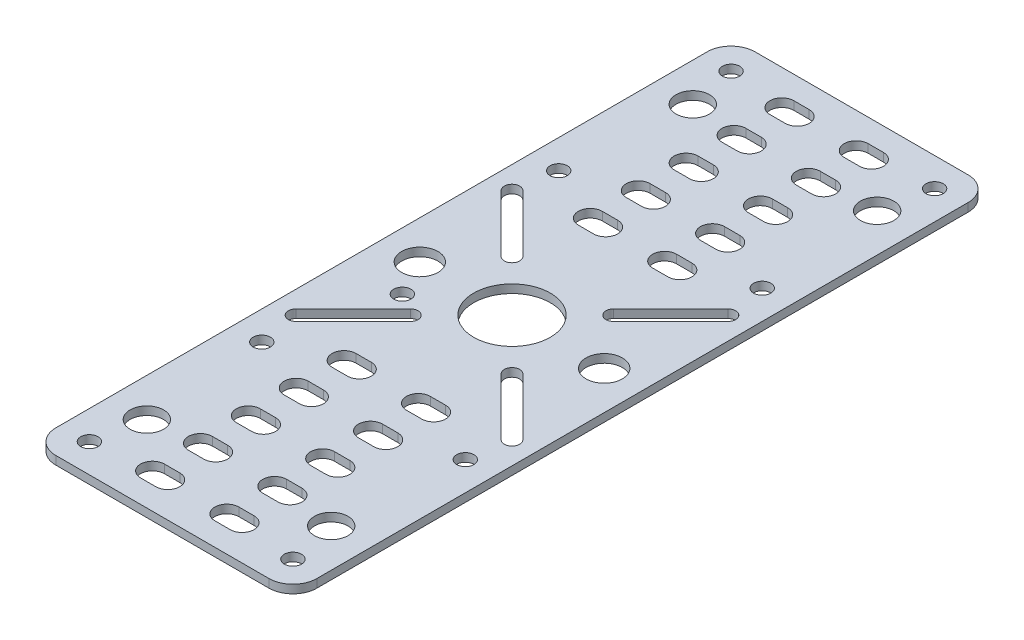
SolidWorks part; units mm, degrees
ref_plane "Front Plane" through (0, 0, 0) normal (0, 0, 1) x (1, 0, 0)
ref_plane "Top Plane" through (0, 0, 0) normal (0, 1, 0) x (1, 0, 0)
ref_plane "Right Plane" through (0, 0, 0) normal (1, 0, 0) x (0, 0, -1)
sketch "Sketch1" plane through (0, 0, 0) normal (0, 1, 0) x (1, 0, 0)
  line L1 (-27.25, 73) -> (27.25, 73)
  line L3 (-27.25, -73) -> (27.25, -73)
  line L5 (-27.25, 73) -> (27.25, -73) construction
  line L6 (-27.25, -73) -> (27.25, 73) construction
  line L9 (-27.25, 73) -> (-27.25, -73)
  line L13 (27.25, 73) -> (27.25, -73)
  point P0 (0, 0)
  dimension "D1" = 54.5
  dimension "D2" = 146
extrude "Boss-Extrude1" add sketch "Sketch1" along normal blind 1.75
sketch "Sketch2" plane through (0, 1.75, 0) normal (0, 1, 0) x (1, 0, 0)
  line L0 (0, 0) -> (-64.534, 64.534) construction
  line L1 (0, 0) -> (0, 55.3558) construction
  line L2 (0, 0) -> (-65.3333, 0) construction
  line L3 (-10.6066, 10.6066) -> (-22.55, 22.55) construction
  line L4 (-11.738, 9.4752) -> (-23.6814, 21.4186)
  line L5 (-9.4752, 11.738) -> (-21.4186, 23.6814)
  line L6 (10.6066, 10.6066) -> (22.55, 22.55) construction
  line L7 (11.738, 9.4752) -> (23.6814, 21.4186)
  line L8 (9.4752, 11.738) -> (21.4186, 23.6814)
  line L9 (-10.6066, -10.6066) -> (-22.55, -22.55) construction
  line L10 (-11.738, -9.4752) -> (-23.6814, -21.4186)
  line L11 (-9.4752, -11.738) -> (-21.4186, -23.6814)
  line L12 (10.6066, -10.6066) -> (22.55, -22.55) construction
  line L13 (11.738, -9.4752) -> (23.6814, -21.4186)
  line L14 (9.4752, -11.738) -> (21.4186, -23.6814)
  line L15 (-9.3578, 65.7099) -> (-6.1612, 65.7099) construction
  line L16 (-9.3578, 68.2099) -> (-6.1612, 68.2099)
  line L17 (-9.3578, 63.2099) -> (-6.1612, 63.2099)
  line L18 (-9.3578, 55.7099) -> (-6.1612, 55.7099) construction
  line L19 (-9.3578, 58.2099) -> (-6.1612, 58.2099)
  line L20 (-9.3578, 53.2099) -> (-6.1612, 53.2099)
  line L21 (9.3578, 55.7099) -> (6.1612, 55.7099) construction
  line L22 (9.3578, 58.2099) -> (6.1612, 58.2099)
  line L23 (9.3578, 53.2099) -> (6.1612, 53.2099)
  line L24 (-9.3578, 45.7099) -> (-6.1612, 45.7099) construction
  line L25 (-9.3578, 48.2099) -> (-6.1612, 48.2099)
  line L26 (-9.3578, 43.2099) -> (-6.1612, 43.2099)
  line L27 (9.3578, 45.7099) -> (6.1612, 45.7099) construction
  line L28 (9.3578, 48.2099) -> (6.1612, 48.2099)
  line L29 (9.3578, 43.2099) -> (6.1612, 43.2099)
  line L30 (-9.3578, 35.7099) -> (-6.1612, 35.7099) construction
  line L31 (-9.3578, 38.2099) -> (-6.1612, 38.2099)
  line L32 (-9.3578, 33.2099) -> (-6.1612, 33.2099)
  line L33 (9.3578, 65.7099) -> (6.1612, 65.7099) construction
  line L34 (9.3578, 68.2099) -> (6.1612, 68.2099)
  line L35 (9.3578, 63.2099) -> (6.1612, 63.2099)
  line L36 (9.3578, 35.7099) -> (6.1612, 35.7099) construction
  line L37 (9.3578, 38.2099) -> (6.1612, 38.2099)
  line L38 (9.3578, 33.2099) -> (6.1612, 33.2099)
  line L39 (-9.3578, 25.7099) -> (-6.1612, 25.7099) construction
  line L40 (-9.3578, 28.2099) -> (-6.1612, 28.2099)
  line L41 (-9.3578, 23.2099) -> (-6.1612, 23.2099)
  line L42 (9.3578, 25.7099) -> (6.1612, 25.7099) construction
  line L43 (9.3578, 28.2099) -> (6.1612, 28.2099)
  line L44 (9.3578, 23.2099) -> (6.1612, 23.2099)
  line L45 (-9.3578, -65.7099) -> (-6.1612, -65.7099) construction
  line L46 (-9.3578, -68.2099) -> (-6.1612, -68.2099)
  line L47 (-9.3578, -63.2099) -> (-6.1612, -63.2099)
  line L48 (-9.3578, -55.7099) -> (-6.1612, -55.7099) construction
  line L49 (-9.3578, -58.2099) -> (-6.1612, -58.2099)
  line L50 (-9.3578, -53.2099) -> (-6.1612, -53.2099)
  line L51 (9.3578, -55.7099) -> (6.1612, -55.7099) construction
  line L52 (9.3578, -58.2099) -> (6.1612, -58.2099)
  line L53 (9.3578, -53.2099) -> (6.1612, -53.2099)
  line L54 (-9.3578, -45.7099) -> (-6.1612, -45.7099) construction
  line L55 (-9.3578, -48.2099) -> (-6.1612, -48.2099)
  line L56 (-9.3578, -43.2099) -> (-6.1612, -43.2099)
  line L57 (9.3578, -45.7099) -> (6.1612, -45.7099) construction
  line L58 (9.3578, -48.2099) -> (6.1612, -48.2099)
  line L59 (9.3578, -43.2099) -> (6.1612, -43.2099)
  line L60 (-9.3578, -35.7099) -> (-6.1612, -35.7099) construction
  line L61 (-9.3578, -38.2099) -> (-6.1612, -38.2099)
  line L62 (-9.3578, -33.2099) -> (-6.1612, -33.2099)
  line L63 (9.3578, -65.7099) -> (6.1612, -65.7099) construction
  line L64 (9.3578, -68.2099) -> (6.1612, -68.2099)
  line L65 (9.3578, -63.2099) -> (6.1612, -63.2099)
  line L66 (9.3578, -35.7099) -> (6.1612, -35.7099) construction
  line L67 (9.3578, -38.2099) -> (6.1612, -38.2099)
  line L68 (9.3578, -33.2099) -> (6.1612, -33.2099)
  line L69 (-9.3578, -25.7099) -> (-6.1612, -25.7099) construction
  line L70 (-9.3578, -28.2099) -> (-6.1612, -28.2099)
  line L71 (-9.3578, -23.2099) -> (-6.1612, -23.2099)
  line L72 (9.3578, -25.7099) -> (6.1612, -25.7099) construction
  line L73 (9.3578, -28.2099) -> (6.1612, -28.2099)
  line L74 (9.3578, -23.2099) -> (6.1612, -23.2099)
  arc A0 (-11.738, 9.4752) -> (-9.4752, 11.738) centre (-10.6066, 10.6066) ccw
  arc A1 (-21.4186, 23.6814) -> (-23.6814, 21.4186) centre (-22.55, 22.55) ccw
  arc A2 (11.738, 9.4752) -> (9.4752, 11.738) centre (10.6066, 10.6066) cw
  arc A3 (21.4186, 23.6814) -> (23.6814, 21.4186) centre (22.55, 22.55) cw
  arc A4 (-11.738, -9.4752) -> (-9.4752, -11.738) centre (-10.6066, -10.6066) cw
  arc A5 (-21.4186, -23.6814) -> (-23.6814, -21.4186) centre (-22.55, -22.55) cw
  arc A6 (11.738, -9.4752) -> (9.4752, -11.738) centre (10.6066, -10.6066) ccw
  arc A7 (21.4186, -23.6814) -> (23.6814, -21.4186) centre (22.55, -22.55) ccw
  circle A8 centre (-19.25, 57) radius 3.5
  circle A9 centre (-19.25, 0) radius 3.796
  circle A10 centre (-19.25, -57) radius 3.5
  circle A11 centre (19.25, -57) radius 3.5
  circle A12 centre (19.25, 0) radius 3.796
  circle A13 centre (19.25, 57) radius 3.5
  arc A14 (-9.3578, 68.2099) -> (-9.3578, 63.2099) centre (-9.3578, 65.7099) ccw
  arc A15 (-6.1612, 63.2099) -> (-6.1612, 68.2099) centre (-6.1612, 65.7099) ccw
  arc A16 (-9.3578, 58.2099) -> (-9.3578, 53.2099) centre (-9.3578, 55.7099) ccw
  arc A17 (-6.1612, 53.2099) -> (-6.1612, 58.2099) centre (-6.1612, 55.7099) ccw
  arc A18 (9.3578, 58.2099) -> (9.3578, 53.2099) centre (9.3578, 55.7099) cw
  arc A19 (6.1612, 53.2099) -> (6.1612, 58.2099) centre (6.1612, 55.7099) cw
  arc A20 (-9.3578, 48.2099) -> (-9.3578, 43.2099) centre (-9.3578, 45.7099) ccw
  arc A21 (-6.1612, 43.2099) -> (-6.1612, 48.2099) centre (-6.1612, 45.7099) ccw
  arc A22 (9.3578, 48.2099) -> (9.3578, 43.2099) centre (9.3578, 45.7099) cw
  arc A23 (6.1612, 43.2099) -> (6.1612, 48.2099) centre (6.1612, 45.7099) cw
  arc A24 (-9.3578, 38.2099) -> (-9.3578, 33.2099) centre (-9.3578, 35.7099) ccw
  arc A25 (-6.1612, 33.2099) -> (-6.1612, 38.2099) centre (-6.1612, 35.7099) ccw
  arc A26 (9.3578, 68.2099) -> (9.3578, 63.2099) centre (9.3578, 65.7099) cw
  arc A27 (6.1612, 63.2099) -> (6.1612, 68.2099) centre (6.1612, 65.7099) cw
  arc A28 (9.3578, 38.2099) -> (9.3578, 33.2099) centre (9.3578, 35.7099) cw
  arc A29 (6.1612, 33.2099) -> (6.1612, 38.2099) centre (6.1612, 35.7099) cw
  arc A30 (-9.3578, 28.2099) -> (-9.3578, 23.2099) centre (-9.3578, 25.7099) ccw
  arc A31 (-6.1612, 23.2099) -> (-6.1612, 28.2099) centre (-6.1612, 25.7099) ccw
  arc A32 (9.3578, 28.2099) -> (9.3578, 23.2099) centre (9.3578, 25.7099) cw
  arc A33 (6.1612, 23.2099) -> (6.1612, 28.2099) centre (6.1612, 25.7099) cw
  arc A34 (-9.3578, -68.2099) -> (-9.3578, -63.2099) centre (-9.3578, -65.7099) cw
  arc A35 (-6.1612, -63.2099) -> (-6.1612, -68.2099) centre (-6.1612, -65.7099) cw
  arc A36 (-9.3578, -58.2099) -> (-9.3578, -53.2099) centre (-9.3578, -55.7099) cw
  arc A37 (-6.1612, -53.2099) -> (-6.1612, -58.2099) centre (-6.1612, -55.7099) cw
  arc A38 (9.3578, -58.2099) -> (9.3578, -53.2099) centre (9.3578, -55.7099) ccw
  arc A39 (6.1612, -53.2099) -> (6.1612, -58.2099) centre (6.1612, -55.7099) ccw
  arc A40 (-9.3578, -48.2099) -> (-9.3578, -43.2099) centre (-9.3578, -45.7099) cw
  arc A41 (-6.1612, -43.2099) -> (-6.1612, -48.2099) centre (-6.1612, -45.7099) cw
  arc A42 (9.3578, -48.2099) -> (9.3578, -43.2099) centre (9.3578, -45.7099) ccw
  arc A43 (6.1612, -43.2099) -> (6.1612, -48.2099) centre (6.1612, -45.7099) ccw
  arc A44 (-9.3578, -38.2099) -> (-9.3578, -33.2099) centre (-9.3578, -35.7099) cw
  arc A45 (-6.1612, -33.2099) -> (-6.1612, -38.2099) centre (-6.1612, -35.7099) cw
  arc A46 (9.3578, -68.2099) -> (9.3578, -63.2099) centre (9.3578, -65.7099) ccw
  arc A47 (6.1612, -63.2099) -> (6.1612, -68.2099) centre (6.1612, -65.7099) ccw
  arc A48 (9.3578, -38.2099) -> (9.3578, -33.2099) centre (9.3578, -35.7099) ccw
  arc A49 (6.1612, -33.2099) -> (6.1612, -38.2099) centre (6.1612, -35.7099) ccw
  arc A50 (-9.3578, -28.2099) -> (-9.3578, -23.2099) centre (-9.3578, -25.7099) cw
  arc A51 (-6.1612, -23.2099) -> (-6.1612, -28.2099) centre (-6.1612, -25.7099) cw
  arc A52 (9.3578, -28.2099) -> (9.3578, -23.2099) centre (9.3578, -25.7099) ccw
  arc A53 (6.1612, -23.2099) -> (6.1612, -28.2099) centre (6.1612, -25.7099) ccw
  circle A62 centre (0, 0) radius 8
  point P7 (-16.5783, 16.5783)
  point P14 (16.5783, 16.5783)
  point P21 (-16.5783, -16.5783)
  point P28 (16.5783, -16.5783)
  point P47 (-7.7595, 65.7099)
  point P58 (-7.7595, 55.7099)
  point P65 (7.7595, 55.7099)
  point P72 (-7.7595, 45.7099)
  point P79 (7.7595, 45.7099)
  point P86 (-7.7595, 35.7099)
  point P89 (7.7595, 65.7099)
  point P98 (7.7595, 35.7099)
  point P105 (-7.7595, 25.7099)
  point P112 (7.7595, 25.7099)
  point P117 (-7.7595, -65.7099)
  point P124 (-7.7595, -55.7099)
  point P131 (7.7595, -55.7099)
  point P138 (-7.7595, -45.7099)
  point P145 (7.7595, -45.7099)
  point P152 (-7.7595, -35.7099)
  point P159 (7.7595, -65.7099)
  point P166 (7.7595, -35.7099)
  point P173 (-7.7595, -25.7099)
  point P180 (7.7595, -25.7099)
  dimension "D1" = 3.2
  dimension "D4" = 7
  dimension "D9" = 16
  dimension "D2" = 15
  dimension "D3" = 45.1
  dimension "D5" = 19.25
  dimension "D6" = 57
  dimension "D7" = 5
  dimension "D8" = 5
extrude "Cut-Extrude1" cut sketch "Sketch2" against normal through all
hole_wizard "M3 Clearance Hole1" positions "Sketch4" profile "Sketch3" hole size "M3" standard "ANSI Metric" end condition through all
sketch "Sketch4" plane through (0, 1.75, 0) normal (0, 1, 0) x (1, 0, 0)
  line L0 (-27.25, 73) -> (-27.25, -73) construction
  line L1 (27.25, 73) -> (-27.25, 73) construction
  line L2 (0, 0) -> (0, 88.6836) construction
  line L4 (0, 0) -> (-50.3697, 0) construction
  line L5 (-23.6814, -23.6814) -> (0, 0) construction
  line L7 (23.6814, -23.6814) -> (0, 0) construction
  line L9 (-15.25, -15.25) -> (15.25, -15.25) construction
  arc A0 (-23.6814, -21.4186) -> (-21.4186, -23.6814) centre (-22.55, -22.55) ccw construction
  arc A1 (21.4186, -23.6814) -> (23.6814, -21.4186) centre (22.55, -22.55) ccw construction
  point P0 (-21.25, 67)
  point P20 (21.25, -67)
  point P21 (-21.25, -67)
  point P30 (-21.25, 31)
  point P35 (21.25, 67)
  point P36 (21.25, 31)
  point P38 (21.25, -31)
  point P39 (-21.25, -31)
  point P63 (-15.25, -7.65)
  dimension "D1" = 6
  dimension "D2" = 6
  dimension "D3" = 31
  dimension "D4" = 30.5
  dimension "D5" = 7.6
sketch "Sketch3" plane through (-21.25, 1.75, -67) normal (1, 0, 0) x (0, 0, 1)
  line L0 (0, 0) -> (0, 1.75)
  line L1 (0, 1.75) -> (1.8, 1.75)
  line L2 (1.8, 1.75) -> (1.8, 0)
  line L5 (1.8, 0) -> (0, 0)
  line L11 (0, -6.35) -> (0, 107.95) construction
  dimension "Thru Hole Dia." = 3.6
  dimension "Thru Hole Depth" = 1.75
fillet "Fillet1" radius 5 4 edges at (27.25, 0.875, -73) (27.25, 0.875, 73) (-27.25, 0.875, -73) (-27.25, 0.875, 73)
